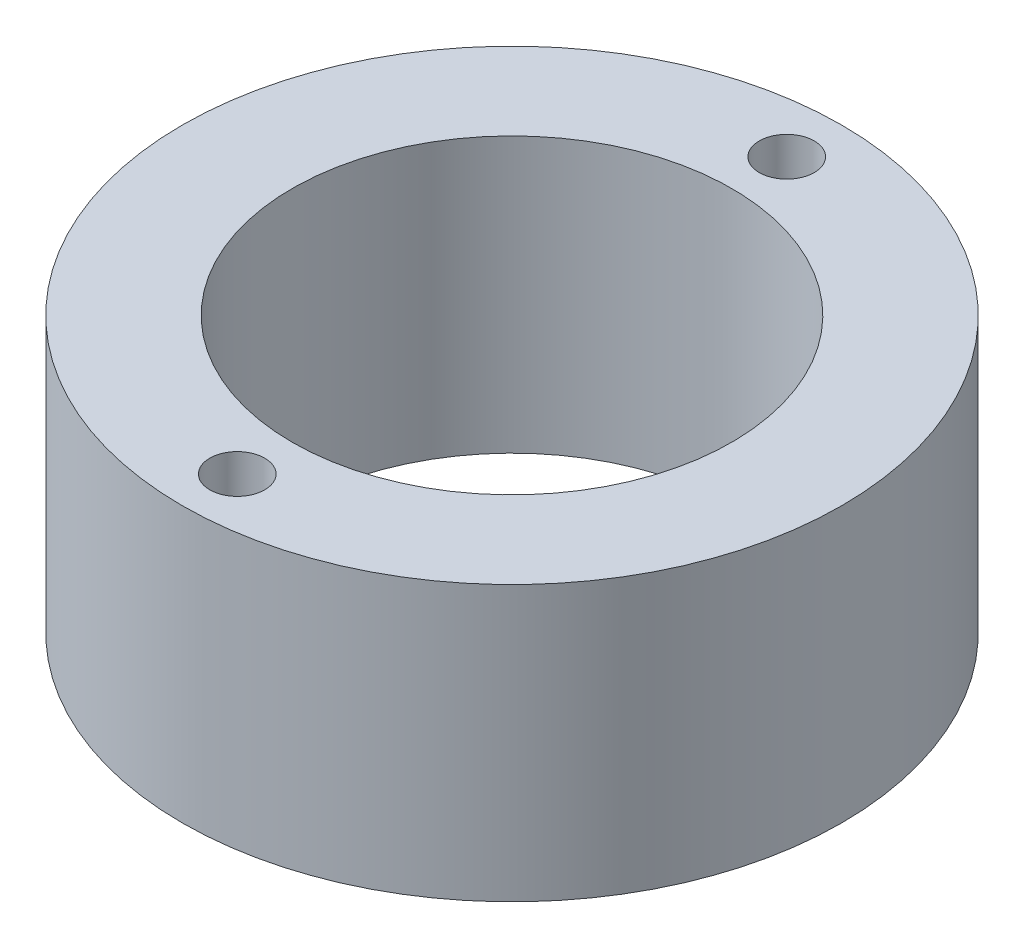
SolidWorks part; units mm, degrees
ref_plane "Front Plane" through (0, 0, 0) normal (0, 0, 1) x (1, 0, 0)
ref_plane "Top Plane" through (0, 0, 0) normal (0, 1, 0) x (1, 0, 0)
ref_plane "Right Plane" through (0, 0, 0) normal (1, 0, 0) x (0, 0, -1)
sketch "Sketch1" plane through (0, 0, 0) normal (0, 1, 0) x (1, 0, 0)
  line L0 (0, 10.9584) -> (0, -8.315) construction
  circle A0 centre (0, 0) radius 4
  circle A1 centre (0, 0) radius 6
  circle A4 centre (0, 5) radius 0.5
  circle A5 centre (0, -5) radius 0.5
  dimension "D1" = 8
  dimension "D2" = 12
  dimension "D3" = 1
  dimension "D4" = 5
  dimension "D5" = 5
extrude "Boss-Extrude1" add sketch "Sketch1" along normal blind 5
